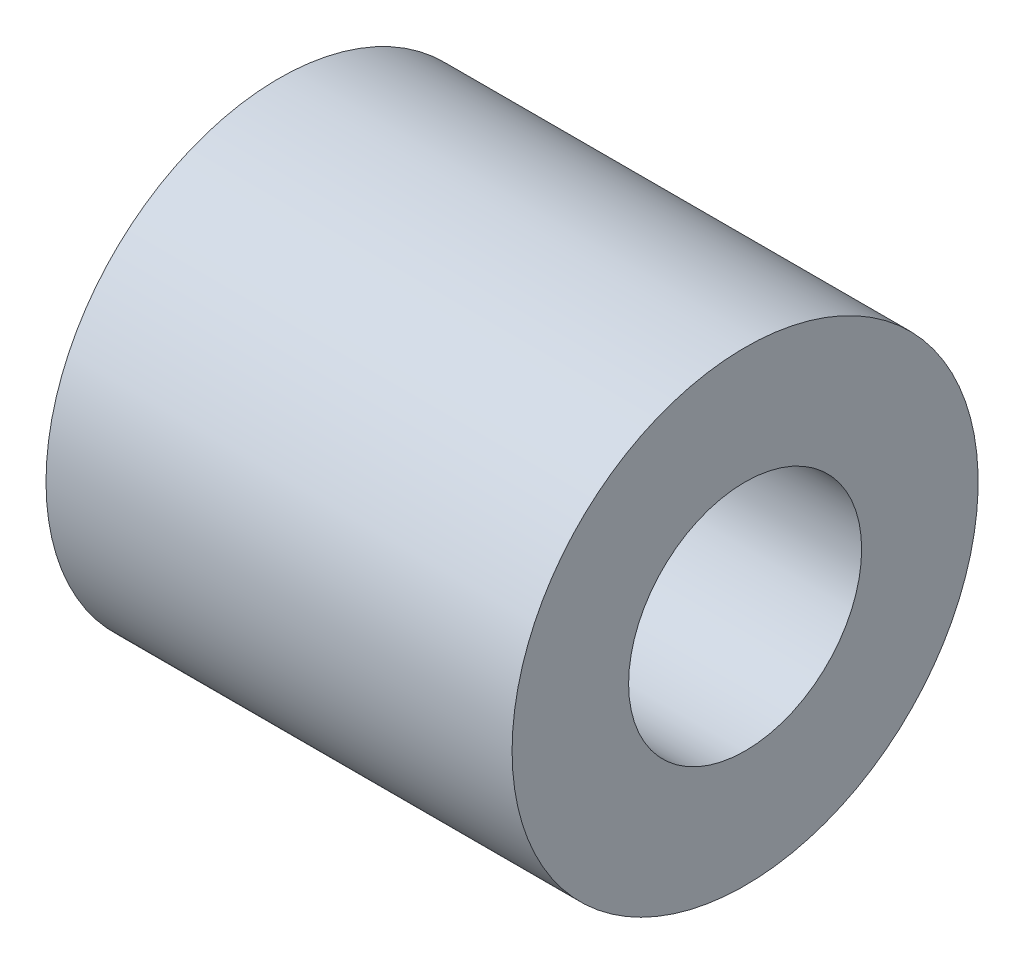
SolidWorks part; units mm, degrees
ref_plane "Front Plane" through (0, 0, 0) normal (0, 0, 1) x (1, 0, 0)
ref_plane "Top Plane" through (0, 0, 0) normal (0, 1, 0) x (1, 0, 0)
ref_plane "Right Plane" through (0, 0, 0) normal (1, 0, 0) x (0, 0, -1)
sketch "Sketch1" plane through (0, 0, 0) normal (0, 1, 0) x (1, 0, 0)
  line L0 (0, 0) -> (4913.3225, 0) construction
  line L1 (0, 0) -> (0, 2.5)
  line L2 (0, 2.5) -> (5, 2.5)
  line L3 (5, 2.5) -> (5, 1.25)
  line L4 (5, 1.25) -> (2, 1.25)
  line L5 (2, 1.25) -> (2, 0)
  line L6 (2, 0) -> (0, 0)
  dimension "D1" = 1.25
  dimension "D2" = 3
  dimension "D3" = 2.5
  dimension "D4" = 2
revolve "Revolve1" add sketch "Sketch1" angle 360 about L0
